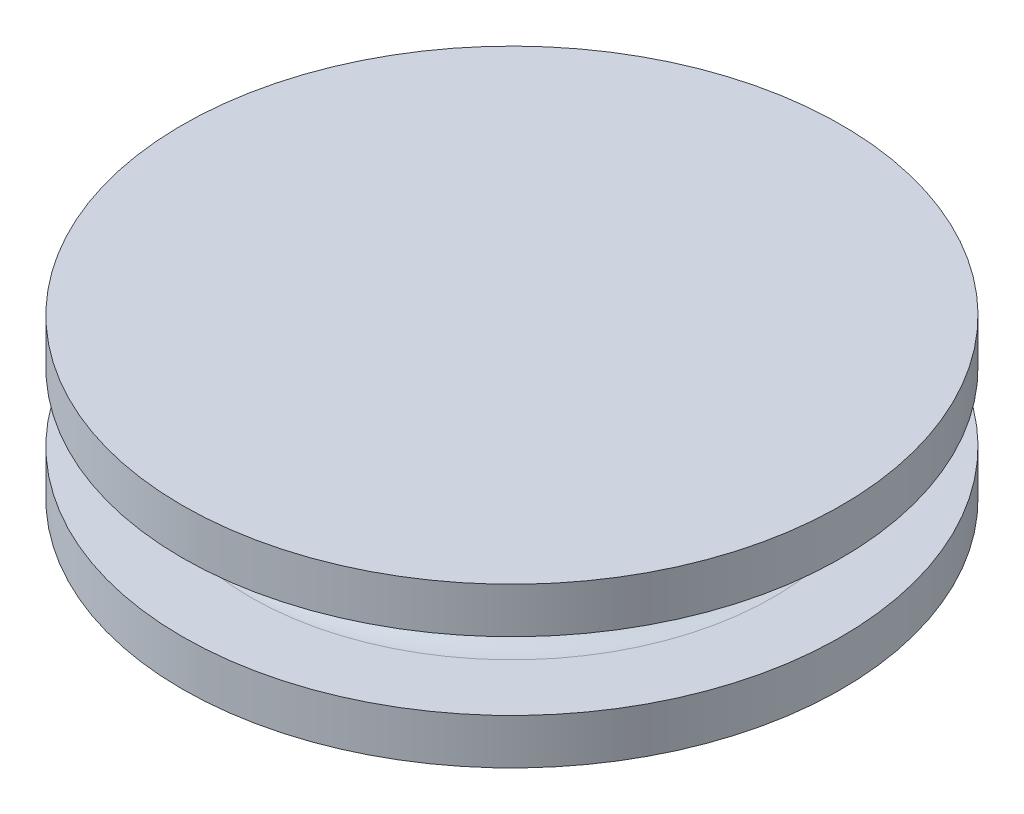
SolidWorks part; units mm, degrees
material "ABS"
ref_plane "正面" through (0, 0, 0) normal (0, 0, 1) x (1, 0, 0)
ref_plane "平面" through (0, 0, 0) normal (0, 1, 0) x (1, 0, 0)
ref_plane "右側面" through (0, 0, 0) normal (1, 0, 0) x (0, 0, -1)
sketch "ｽｹｯﾁ1" plane through (0, 0, 0) normal (0, 0, 1) x (1, 0, 0)
  line L0 (0, 0) -> (0, 6) construction
  line L1 (0, 3.5) -> (-14.5, 3.5)
  line L2 (-14.5, 3.5) -> (-14.5, 1.5)
  line L3 (-14.5, 1.5) -> (-11.5, 1.5)
  line L4 (-10, 0) -> (0, 0) construction
  line L5 (-14.5, -3.5) -> (-14.5, -1.5)
  line L6 (-14.5, -1.5) -> (-11.5, -1.5)
  line L7 (0, -3.5) -> (-14.5, -3.5)
  line L8 (0, 3.5) -> (0, -3.5)
  arc A0 (-11.5, 1.5) -> (-11.5, -1.5) centre (-11.5, 0) cw
  point P9 (-4, 1.1905)
  point P10 (0, 0)
  point P11 (-2.4756, 1.7695)
  point P12 (0, 0)
  point P13 (0, 0)
  point P18 (-2.7682, -1.5)
  point P19 (0, 0)
  dimension "D1" = 3.5
  dimension "D2" = 1.5
  dimension "D3" = 10
  dimension "D4" = 3
revolve "回転1" add sketch "ｽｹｯﾁ1" angle 360 about L8
